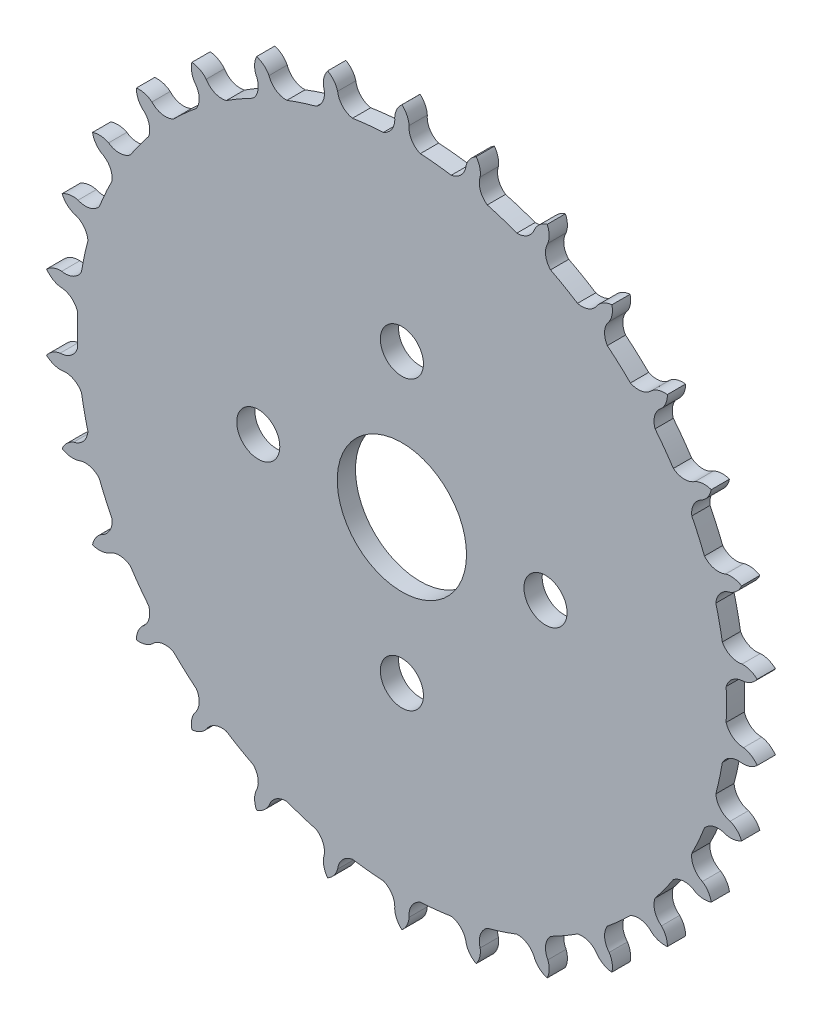
SolidWorks part; units mm, degrees
ref_plane "Front Plane" through (0, 0, 0) normal (0, 0, 1) x (1, 0, 0)
ref_plane "Top Plane" through (0, 0, 0) normal (0, 1, 0) x (1, 0, 0)
ref_plane "Right Plane" through (0, 0, 0) normal (1, 0, 0) x (0, 0, -1)
sketch "Sketch1" plane through (0, 0, 0) normal (0, 0, 1) x (1, 0, 0)
  circle A0 centre (0, 10) radius 1.5
  circle A1 centre (0, 0) radius 22.6042
  circle A6 centre (0, 0) radius 4.5
  circle A7 centre (10, 0) radius 1.5
  circle A8 centre (0, -10) radius 1.5
  circle A9 centre (-10, 0) radius 1.5
  dimension "D1" = 4
extrude "Boss-Extrude2" add sketch "Sketch1" along normal blind 1.27
sketch "Sketch2" plane through (0, 0, 1.27) normal (0, 0, 1) x (1, 0, 0)
  arc A0 (0, 24.8732) -> (-0.5, 23.868) centre (0.9512, 23.7732) ccw
  arc A1 (0, 24.8732) -> (0.5, 23.868) centre (-0.9512, 23.7732) cw
  arc A2 (-0.5, 23.868) -> (-1.6391, 22.4794) centre (-1.7638, 23.7433) cw
  arc A3 (0.5, 23.868) -> (1.6391, 22.4794) centre (1.7638, 23.7433) ccw
  arc A4 (-1.6391, 22.4794) -> (1.6391, 22.4794) centre (0, 31.849) ccw
extrude "Boss-Extrude4" add sketch "Sketch2" against normal blind 1.27
pattern_circular "CirPattern1" count 30 over 360 about axis through (0, 0, 0) along (0, 0, 1) of "Boss-Extrude4"
